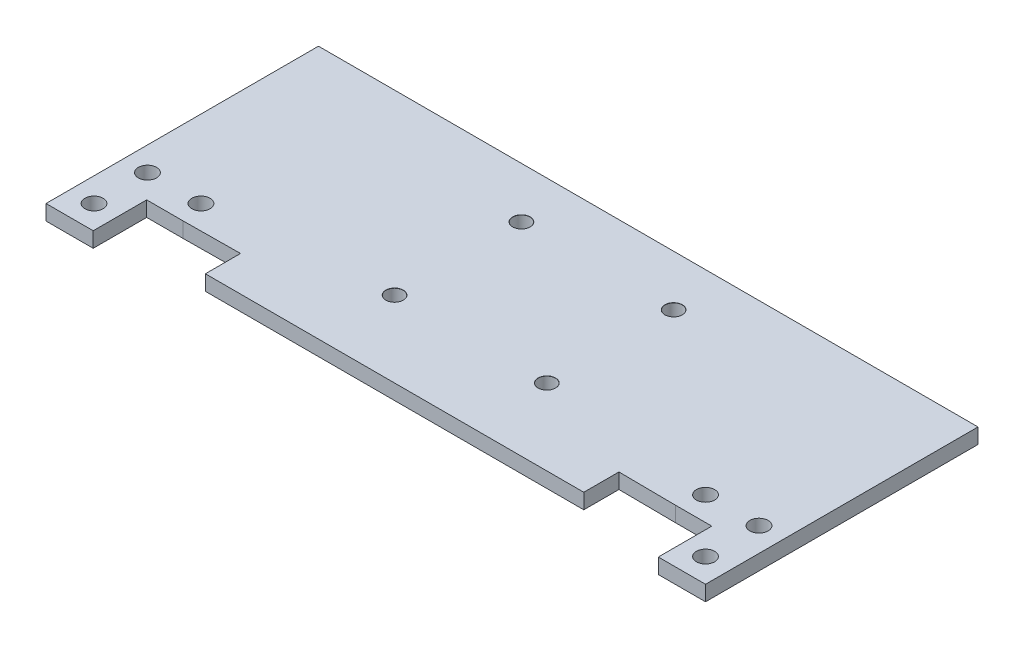
SolidWorks part; units mm, degrees
ref_plane "Front Plane" through (0, 0, 0) normal (0, 0, 1) x (1, 0, 0)
ref_plane "Top Plane" through (0, 0, 0) normal (0, 1, 0) x (1, 0, 0)
ref_plane "Right Plane" through (0, 0, 0) normal (1, 0, 0) x (0, 0, -1)
sketch "Sketch1" plane through (0, 0, 0) normal (1, 0, 0) x (0, 0, -1)
  line L2 (0, 3) -> (50, 3)
  line L6 (0, 0) -> (50, 0)
  line L7 (50, 0) -> (50, 3)
  line L8 (0, 3) -> (0, 0)
  point P0 (0, 0)
  dimension "D3" = 50
  dimension "D6" = 3
extrude "Boss-Extrude1" add sketch "Sketch1" along normal blind 130
hole_wizard "M3 Clearance Hole2" positions "Sketch5" profile "Sketch6" hole size "M3" standard "ANSI Metric" end condition through all
sketch "Sketch5" plane through (0, 3, 0) normal (0, 1, 0) x (1, 0, 0)
  line L0 (65, 50) -> (65, 40) construction
  line L1 (130, 50) -> (0, 50) construction
  line L3 (50, 40) -> (80, 40) construction
  line L4 (80, 40) -> (80, 15) construction
  line L5 (80, 15) -> (50, 15) construction
  line L6 (50, 15) -> (50, 40) construction
  point P9 (50, 40)
  point P11 (80, 40)
  point P13 (50, 15)
  point P15 (80, 15)
  point P25 (65, 40)
  point P26 (0, 0)
  point P27 (0, 0)
  point P29 (65, 45)
  dimension "D1" = 30
  dimension "D2" = 25
  dimension "D3" = 10
sketch "Sketch6" plane through (80, 3, -15) normal (1, 0, 0) x (0, 0, 1)
  line L0 (0, 0) -> (0, 3)
  line L1 (0, 3) -> (1.7, 3)
  line L2 (1.7, 3) -> (1.7, 0.025)
  line L3 (1.7, 0.025) -> (1.725, 0)
  line L5 (1.725, 0) -> (0, 0)
  line L6 (-1.7, 0.025) -> (-1.725, 0) construction
  line L11 (0, -6.35) -> (0, 107.95) construction
  dimension "Thru Hole Dia." = 3.4
  dimension "Thru Hole Depth" = 3
  dimension "Near C'Sink Dia." = 3.45
  dimension "Near C'Sink Angle" = 90
sketch "Sketch7" plane through (0, 0, 0) normal (0, -1, 0) x (1, 0, 0)
  line L0 (130, 0) -> (0, 0) construction
  line L1 (130, 0) -> (0, 0)
  line L2 (120.6956, 0) -> (120.6956, 3.7101)
  line L3 (120.6956, 3.7101) -> (130, 3.7101)
  line L4 (130, 16.7101) -> (130, -16.2899) construction
  line L5 (130, 3.7101) -> (130, 0)
  line L6 (125.2699, -1.02) -> (130, -1.02) construction
  line L7 (130, 0) -> (130, -50) construction
  line L8 (125.3478, 3.7101) -> (125.3478, -1.02) construction
  line L9 (120.4956, -6.6297) -> (120.4956, 8.0593) construction
  line L10 (120.4956, -6.6297) -> (120.4956, 8.0593) construction
  line L11 (65, 0) -> (65, -50) construction
  line L12 (130, -50) -> (0, -50) construction
  line L13 (0, 3.7101) -> (0, 0)
  line L14 (9.3044, 3.7101) -> (0, 3.7101)
  line L15 (9.3044, 0) -> (9.3044, 3.7101)
  circle A0 centre (125.2699, -1.02) radius 1.8 construction
  circle A1 centre (125.2699, -1.02) radius 1.8 construction
  line M17 (130, 0) -> (0, 0)
  dimension "D1" = 0.2
extrude "Boss-Extrude2" add sketch "Sketch7" against normal up to surface (3 mm away) contours L5 L3 L2 M17 | L15 L14 L13 M17 up to face at (50, 3, -38.275)
sketch "Sketch9" plane through (0, 3, 0) normal (0, 1, 0) x (1, 0, 0)
  line L0 (120.4956, 6.6297) -> (113.4956, 6.6297) construction
  line L1 (120.4956, 6.6297) -> (120.4956, -8.0593) construction
  line L2 (120.4956, 6.6297) -> (113.4956, 6.6297)
  line L3 (120.4956, 6.6297) -> (120.4956, -8.0593)
  line L4 (102.4956, -2.7203) -> (102.4956, 6.7276) construction
  line L5 (102.4956, -2.7203) -> (102.4956, 6.7276)
  line L6 (113.4956, 6.6297) -> (102.4956, 6.7276)
  line L7 (102.4956, -2.7203) -> (120.4956, -8.0593)
  line L8 (102.2956, -2.8696) -> (102.2956, 6.9294)
  line L9 (113.4965, 6.8297) -> (102.2956, 6.9294)
  line L10 (120.6956, 6.8297) -> (113.4965, 6.8297)
  line L11 (120.6956, 6.8297) -> (120.6956, -8.3273)
  line L12 (102.2956, -2.8696) -> (120.6956, -8.3273)
  line L13 (120.6956, 0) -> (9.3044, 0) construction
  line L14 (130, 50) -> (0, 50) construction
  line L15 (120.6956, 0) -> (9.3044, 0) construction
  line L16 (130, 50) -> (0, 50) construction
  line L17 (65, 50) -> (65, 0) construction
  line L18 (9.3044, 6.8297) -> (9.3044, -8.3273)
  line L19 (9.3044, 6.8297) -> (16.5035, 6.8297)
  line L20 (16.5035, 6.8297) -> (27.7044, 6.9294)
  line L21 (27.7044, -2.8696) -> (27.7044, 6.9294)
  line L22 (27.7044, -2.8696) -> (9.3044, -8.3273)
  line M8 (9.3044, -3.7101) -> (9.3044, 0)
  line M9 (9.3044, 0) -> (120.6956, 0)
  line M10 (120.6956, 0) -> (120.6956, -3.7101)
  dimension "D1" = 0.2
extrude "Cut-Extrude1" cut sketch "Sketch9" against normal through all contours L2 L6 L5 L3 M9 | L5 L7 L3 M9 | L8 L12 L11 L3 L7 L5 M10 M9 | L11 L10 L9 L8 L5 L6 L2 L3 M9 | L21 L20 L19 L18 M9 | L22 L21 L18 M9 M8
sketch "Sketch10" plane through (0, 3, 0) normal (0, 1, 0) x (1, 0, 0)
  point P0 (125.2699, 1.02)
  point P3 (125.2699, 11.5598)
  point P6 (114.7301, 11.5598)
hole_wizard "M3 Clearance Hole3" positions "Sketch10" profile "Sketch11" hole size "M3" standard "ANSI Metric" end condition through all
sketch "Sketch11" plane through (125.2699, 3, -1.02) normal (1, 0, 0) x (0, 0, 1)
  line L0 (0, 0) -> (0, 3)
  line L1 (0, 3) -> (1.8, 3)
  line L2 (1.8, 3) -> (1.8, 0)
  line L5 (1.8, 0) -> (0, 0)
  line L11 (0, -6.35) -> (0, 107.95) construction
  dimension "Thru Hole Dia." = 3.6
  dimension "Thru Hole Depth" = 3
ref_plane "Plane1" through (65, 0, 0) normal (1, 0, 0) x (0, 0, -1)
mirror "Mirror1" about plane through (65, 0, 0) normal (1, 0, 0) of "M3 Clearance Hole3"
